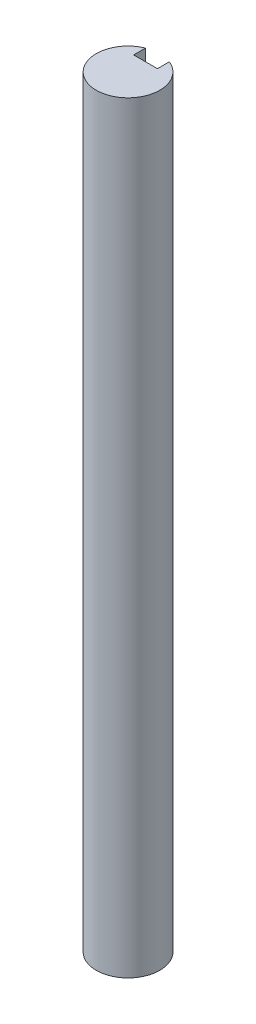
SolidWorks part; units mm, degrees
material "1023 Carbon Steel Sheet (SS)"
ref_plane "Front Plane" through (0, 0, 0) normal (0, 0, 1) x (1, 0, 0)
ref_plane "Top Plane" through (0, 0, 0) normal (0, 1, 0) x (1, 0, 0)
ref_plane "Right Plane" through (0, 0, 0) normal (1, 0, 0) x (0, 0, -1)
sketch "Sketch1" plane through (0, 0, 0) normal (0, 1, 0) x (1, 0, 0)
  line L0 (-1.1906, 2.9433) -> (-1.1906, 1.7527)
  line L1 (-1.1906, 1.7527) -> (1.1906, 1.7527)
  line L2 (1.1906, 1.7527) -> (1.1906, 2.9433)
  arc A0 (-1.1906, 2.9433) -> (1.1906, 2.9433) centre (0, 0) ccw
  point P5 (0, 1.7527)
  dimension "D1" = 6.35
  dimension "D2" = 2.3813
  dimension "D3" = 1.1906
extrude "Boss-Extrude1" add sketch "Sketch1" along normal blind 76.2
